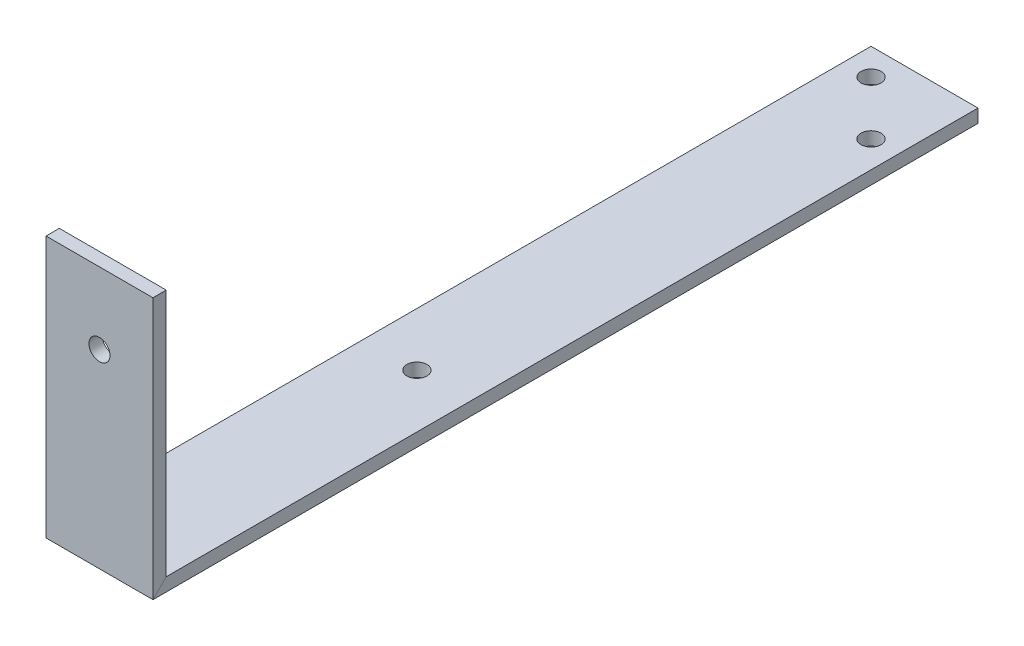
SolidWorks part; units mm, degrees
ref_plane "Alzado" through (0, 0, 0) normal (0, 0, 1) x (1, 0, 0)
ref_plane "Planta" through (0, 0, 0) normal (0, 1, 0) x (1, 0, 0)
ref_plane "Vista lateral" through (0, 0, 0) normal (1, 0, 0) x (0, 0, -1)
sketch "Croquis2" plane through (0, 0, 0) normal (0, 1, 0) x (1, 0, 0)
  line L1 (-25.4, 3.155) -> (25.4, 3.155)
  line L2 (-25.4, 3.155) -> (-25.4, -3.155)
  line L3 (-25.4, -3.155) -> (25.4, -3.155)
  line L4 (25.4, 3.155) -> (25.4, -3.155)
  line L5 (-25.4, 3.155) -> (25.4, -3.155) construction
  line L6 (-25.4, -3.155) -> (25.4, 3.155) construction
  line L7 (184.6, 3.155) -> (235.4, 3.155)
  line L8 (184.6, 3.155) -> (184.6, -3.155)
  line L9 (184.6, -3.155) -> (235.4, -3.155)
  line L10 (235.4, 3.155) -> (235.4, -3.155)
  line L11 (184.6, 3.155) -> (235.4, -3.155) construction
  line L12 (184.6, -3.155) -> (235.4, 3.155) construction
  point P0 (0, 0)
  point P6 (210, 0)
  dimension "D1" = 50.8
  dimension "D2" = 6.31
  dimension "D3" = 210
  dimension "D4" = 50.8
  dimension "D5" = 6.31
sketch3d "Croquis3D1"
  line L0 (0, 0, 0) -> (0, -567.24, 0)
  line L1 (0, -567.24, 0) -> (0, -567.24, 336.2)
  line L2 (0, -567.24, 336.2) -> (1786.7, -567.24, 336.2)
  line L3 (1786.7, -567.24, 336.2) -> (1786.7, -567.24, 693.16)
  line L4 (-25.4, 0, 0) -> (-25.4, -383.9185, 0) construction
  line L5 (-25.4, 0, -3.155) -> (-25.4, 0, 3.155) construction
  line L6 (-25.4, -383.9185, 0) -> (-25.4, -383.9185, 653.2834) construction
  line L7 (1786.7, -567.24, 693.16) -> (1786.7, -436.23, 693.16)
  line L8 (1786.7, -436.23, 693.16) -> (1786.7, -436.23, 1487.1629)
  dimension "D1" = 567.24
  dimension "D2" = 336.2
  dimension "D3" = 1786.7
  dimension "D4" = 356.96
  dimension "D5" = 131.01
  dimension "D6" = 794.0029
sweep "Barrer1" add profiles "Croquis2" path "Croquis3D1"
sketch "Croquis3" plane through (0, 0, -3.155) normal (0, 0, -1) x (-1, 0, 0)
  line L0 (-235.4, 0) -> (-235.4, -6.31)
  line L1 (-235.4, 0) -> (-235.4, -570.395) construction
  line L2 (-235.4, -6.31) -> (-184.6, -6.31)
  line L3 (-184.6, 0) -> (-184.6, -570.395) construction
  line L4 (-184.6, -6.31) -> (-184.6, 0)
  line L5 (-184.6, 0) -> (-235.4, 0)
  line L7 (-25.4, 0) -> (-25.4, -6.31)
  line L8 (-25.4, 0) -> (-25.4, -570.395) construction
  line L9 (-25.4, -6.31) -> (25.4, -6.31)
  line L10 (25.4, 0) -> (25.4, -570.395) construction
  line L11 (25.4, -6.31) -> (25.4, 0)
  line L12 (-25.4, 0) -> (25.4, 0) construction
  line L13 (25.4, 0) -> (-25.4, 0)
  dimension "D1" = 6.31
  dimension "D2" = 6.31
sketch3d "Croquis3D2"
  line L0 (25.4, -3.155, -3.155) -> (-0.201, -3.155, -3.155) construction
  line L1 (25.4, 0, -3.155) -> (25.4, -6.31, -3.155) construction
  line L2 (-0.201, -3.155, -3.155) -> (-0.201, -5.2746, -3.155) construction
  line L3 (-0.201, -3.155, -3.155) -> (-0.201, -3.155, -207.155)
  line L4 (-0.201, -3.155, -207.155) -> (-0.201, -53.155, -207.155)
  dimension "D1" = 204
  dimension "D2" = 50
sweep "Barrer4" add profiles "Croquis3" path "Croquis3D2"
sketch "Croquis4" plane through (0, 0, -210.31) normal (0, 0, -1) x (-1, 0, 0)
  line L0 (-184.6, 0) -> (-184.6, -53.155)
  line L1 (-184.6, -53.155) -> (-124.6, -53.155)
  line L2 (-124.6, -53.155) -> (-124.6, 0)
  line L3 (-124.6, 0) -> (-184.6, 0)
  dimension "D1" = 60
extrude "Saliente-Extruir1" add sketch "Croquis4" against normal blind 6.31
sketch "Croquis5" plane through (0, 0, -204) normal (0, 0, 1) x (1, 0, 0)
  line L0 (184.6, -6.31) -> (124.6, -6.31)
  line L1 (124.6, -53.155) -> (124.6, 0) construction
  line L2 (124.6, -6.31) -> (124.6, 0)
  line L3 (124.6, 0) -> (184.6, 0)
  line L4 (184.6, 0) -> (184.6, -6.31)
extrude "Cortar-Extruir1" cut sketch "Croquis5" against normal blind 6.31
sketch "Croquis6" plane through (0, -433.075, 0) normal (0, 1, 0) x (1, 0, 0)
  circle A0 centre (1285.7, -1260.295) radius 4.75
  circle A1 centre (1495.7, -1260.295) radius 4.75
sketch "Croquis7" plane through (0, 0, 0) normal (0, 1, 0) x (1, 0, 0)
  line L0 (1761.3, -361.6) -> (2022.1, -361.6)
  line L1 (2022.1, -100.8) -> (2022.1, -690.005) construction
  line L2 (2022.1, -361.6) -> (2022.1, 278.6006)
  line L3 (2022.1, 278.6006) -> (-188.1159, 278.6006)
  line L4 (-188.1159, 278.6006) -> (-188.1159, -361.6)
  line L5 (-188.1159, -361.6) -> (1761.3, -361.6)
extrude "Cortar-Extruir2" cut sketch "Croquis7" against normal blind 634
sketch "Croquis8" plane through (0, 0, 361.6) normal (0, 0, -1) x (-1, 0, 0)
  line L0 (-1812.1, -564.085) -> (-1761.3, -564.085)
  line L1 (-1761.3, -564.085) -> (-1761.3, -570.395)
  line L2 (-1761.3, -570.395) -> (-1812.1, -570.395)
  line L3 (-1812.1, -570.395) -> (-1812.1, -564.085)
extrude "Saliente-Extruir2" add sketch "Croquis8" along normal blind 63.5
sketch "Croquis9" plane through (0, -433.075, 0) normal (0, 1, 0) x (1, 0, 0)
  line L0 (1786.7, -1487.1629) -> (1996.7, -1487.1629) construction
  line L1 (1761.3, -1487.1629) -> (1812.1, -1487.1629) construction
  line L2 (1971.3, -1487.1629) -> (2022.1, -1487.1629) construction
  line L3 (1996.7, -1487.1629) -> (1996.7, -1454.1629) construction
  line L4 (1996.7, -1454.1629) -> (1996.7, -1234.1629) construction
  line L5 (1786.7, -1487.1629) -> (1786.7, -1454.1629) construction
  line L6 (1786.7, -1454.1629) -> (1786.7, -1234.1629) construction
  circle A0 centre (1786.7, -1454.1629) radius 5
  circle A1 centre (1786.7, -1234.1629) radius 5
  circle A2 centre (1996.7, -1234.1629) radius 5
  circle A3 centre (1996.7, -1454.1629) radius 5
  dimension "D3" = 10
  dimension "D4" = 10
  dimension "D5" = 10
  dimension "D6" = 10
  dimension "D1" = 33
  dimension "D2" = 220
extrude "Cortar-Extruir3" cut sketch "Croquis9" against normal blind 10
sketch "Croquis10" plane through (2022.1, 0, 0) normal (1, 0, 0) x (0, 0, -1)
  line L0 (-696.315, -439.385) -> (-696.315, -433.075)
  line L1 (-690.005, -433.075) -> (-1487.1629, -433.075) construction
  line L2 (-696.315, -433.075) -> (-1487.1629, -433.075)
  line L3 (-1487.1629, -433.075) -> (-1487.1629, -439.385)
  line L4 (-1487.1629, -439.385) -> (-696.315, -439.385)
extrude "Cortar-Extruir4" cut sketch "Croquis10" against normal blind 286
sketch "Croquis11" plane through (0, -433.075, 0) normal (0, 1, 0) x (1, 0, 0)
  line L0 (2022.1, -696.315) -> (2022.1, -690.005)
  line L1 (2022.1, -690.005) -> (1761.3, -690.005)
  line L2 (1761.3, -690.005) -> (1761.3, -696.315)
  line L3 (1761.3, -696.315) -> (2022.1, -696.315)
  line L4 (2022.1, -696.315) -> (2028.4123, -762.8726)
  line M1 (1971.3, -690.005) -> (1971.3, -696.315)
  line M2 (1971.3, -696.315) -> (2022.1, -696.315)
  line M3 (2022.1, -696.315) -> (2022.1, -690.005)
  line M4 (2022.1, -690.005) -> (1971.3, -690.005)
extrude "Cortar-Extruir5" cut sketch "Croquis11" against normal blind 13.11 contours M4 M1 M2 M3 | L2 L3 L1 M1
sketch "Croquis12" plane through (0, 0, 361.6) normal (0, 0, -1) x (-1, 0, 0)
  line L0 (-2022.1, -564.085) -> (-2022.1, -570.395)
  line L1 (-2022.1, -570.395) -> (-1971.3, -570.395)
  line L2 (-1971.3, -570.395) -> (-1971.3, -564.085)
  line L3 (-1971.3, -564.085) -> (-2022.1, -564.085)
extrude "Saliente-Extruir3" add sketch "Croquis12" along normal blind 6.35
sketch "Croquis13" plane through (0, -564.085, 0) normal (0, 1, 0) x (1, 0, 0)
  line L0 (1812.1, -298.1) -> (1812.1, -304.45)
  line L1 (1812.1, -298.1) -> (1812.1, -690.005) construction
  line L2 (1812.1, -304.45) -> (1761.3, -304.45)
  line L3 (1761.3, -298.1) -> (1761.3, -690.005) construction
  line L4 (1761.3, -304.45) -> (1761.3, -298.1)
  line L5 (1761.3, -298.1) -> (1812.1, -298.1)
  dimension "D1" = 6.35
extrude "Cortar-Extruir6" cut sketch "Croquis13" against normal blind 6.35
sketch "Croquis14" plane through (0, -446.185, 0) normal (0, 1, 0) x (1, 0, 0)
  line L1 (2042.1777, -334.8977) -> (1956.3306, -334.8977)
  line L2 (2042.1777, -334.8977) -> (2042.1777, -808.5369)
  line L3 (2042.1777, -808.5369) -> (1956.3306, -808.5369)
  line L4 (1956.3306, -334.8977) -> (1956.3306, -808.5369)
  line L5 (2042.1777, -334.8977) -> (1956.3306, -808.5369) construction
  line L6 (2042.1777, -808.5369) -> (1956.3306, -334.8977) construction
  point P0 (1999.2542, -571.7173)
extrude "Cortar-Extruir7" cut sketch "Croquis14" against normal blind 137
sketch "Croquis15" plane through (0, -564.085, 0) normal (0, 1, 0) x (1, 0, 0)
  line L0 (1786.7, -545.545) -> (1788.8858, -549.7763) construction
  line L1 (1788.8858, -549.7763) -> (1786.7, -545.545) construction
  circle A0 centre (1786.7, -545.545) radius 4.7625
extrude "Cortar-Extruir8" cut sketch "Croquis15" against normal blind 33
sketch "Croquis16" plane through (0, 0, 690.005) normal (0, 0, -1) x (-1, 0, 0)
  line L0 (-1786.7, -446.185) -> (-1786.7, -480.185) construction
  line L1 (-1812.1, -446.185) -> (-1761.3, -446.185) construction
  line L2 (-1786.7, -567.24) -> (-1786.7, -436.23) construction
  circle A0 centre (-1786.7, -480.185) radius 5
  dimension "D2" = 10
  dimension "D1" = 34
extrude "Cortar-Extruir9" cut sketch "Croquis16" against normal blind 33
sketch "Croquis18" plane through (0, -570.395, 0) normal (0, -1, 0) x (-1, 0, 0)
  circle A0 centre (-1799.4, -342.5522) radius 4.7625
  circle A1 centre (-1774, -317.1522) radius 4.7625
extrude "Cortar-Extruir10" cut sketch "Croquis18" against normal blind 50
